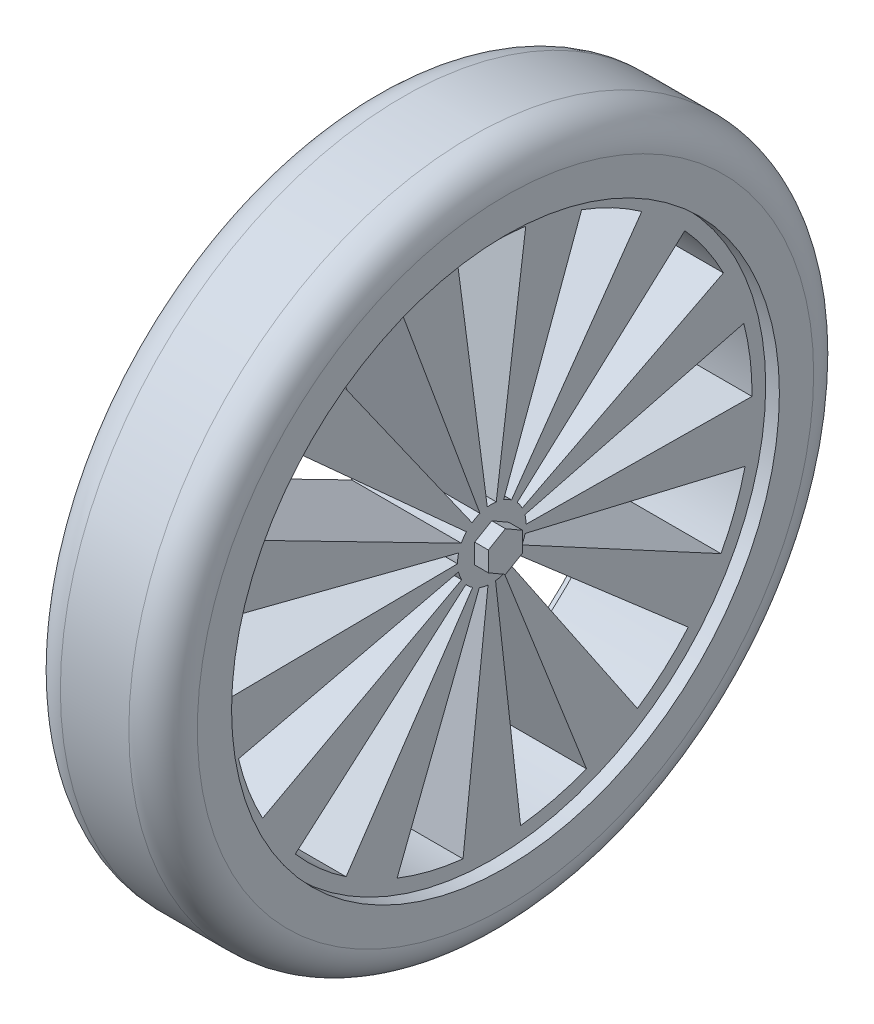
SolidWorks part; units mm, degrees
ref_plane "Front Plane" through (0, 0, 0) normal (0, 0, 1) x (1, 0, 0)
ref_plane "Top Plane" through (0, 0, 0) normal (0, 1, 0) x (1, 0, 0)
ref_plane "Right Plane" through (0, 0, 0) normal (1, 0, 0) x (0, 0, -1)
sketch "Sketch1" plane through (0, 0, 0) normal (1, 0, 0) x (0, 0, -1)
  circle A0 centre (0, 0) radius 50
  dimension "D1" = 100
extrude "Boss-Extrude1" add sketch "Sketch1" along normal blind 20
sketch "Sketch2" plane through (0, 0, 0) normal (-1, 0, 0) x (0, 0, 1)
  circle A2 centre (0, 0) radius 40
  circle A3 centre (0, 0) radius 40
  dimension "D1" = 10
extrude "Cut-Extrude1" cut sketch "Sketch2" against normal blind 2
ref_plane "Plane1" through (10, 0, 0) normal (1, 0, 0) x (0, 0, -1)
mirror "Mirror1" about plane through (10, 0, 0) normal (1, 0, 0) of "Cut-Extrude1"
sketch "Sketch3" plane through (2, 0, 0) normal (-1, 0, 0) x (0, 0, 1)
  line L0 (0, 0) -> (0, 38) construction
  line L1 (0, 0) -> (4.96, 37.6749)
  line L2 (0, 0) -> (-4.96, 37.6749)
  circle A1 centre (0, 0) radius 5
  circle A2 centre (0, 0) radius 38
  circle A3 centre (0, 0) radius 38
  dimension "D2" = 10
  dimension "D3" = 15
  dimension "D4" = 7.5
  dimension "D1" = 2
extrude "Cut-Extrude2" cut sketch "Sketch3" against normal through all contours L0 A1 L1 A3 | A1 L0 A3 L2
pattern_circular "CirPattern1" count 13 over 360 about axis through (0, 0, 0) along (1, 0, 0) of "Cut-Extrude2"
fillet "Fillet1" radius 5 2 edges at (20, 0, -50) (0, 0, -50)
sketch "Sketch4" plane through (2, 0, 0) normal (-1, 0, 0) x (0, 0, 1)
  line L1 (0, -2.8868) -> (2.5, -1.4434)
  line L2 (2.5, -1.4434) -> (2.5, 1.4434)
  line L3 (2.5, 1.4434) -> (0, 2.8868)
  line L4 (0, 2.8868) -> (-2.5, 1.4434)
  line L5 (-2.5, 1.4434) -> (-2.5, -1.4434)
  line L6 (-2.5, -1.4434) -> (0, -2.8868)
  circle A0 centre (0, 0) radius 2.5 construction
  dimension "D1" = 5
extrude "Boss-Extrude2" add sketch "Sketch4" along normal blind 2
mirror "Mirror2" about plane through (10, 0, 0) normal (1, 0, 0) of "Boss-Extrude2"
